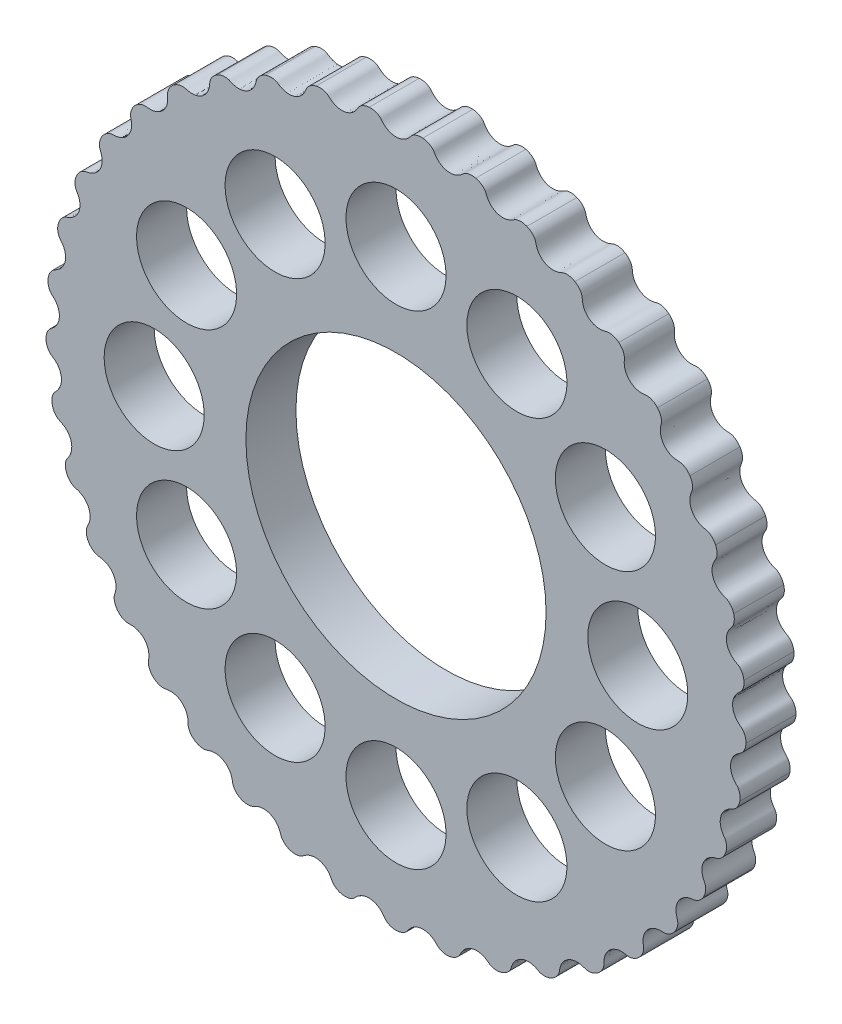
SolidWorks part; units mm, degrees
ref_plane "前视基准面" through (0, 0, 0) normal (0, 0, 1) x (1, 0, 0)
ref_plane "上视基准面" through (0, 0, 0) normal (0, 1, 0) x (1, 0, 0)
ref_plane "右视基准面" through (0, 0, 0) normal (1, 0, 0) x (0, 0, -1)
sketch "Sketch1" plane through (0, 0, 0) normal (0, 0, 1) x (1, 0, 0)
  spline S3 degree 3 number of poles 69 (-8.0377, 104.692) -> (8.0377, 104.692)
  spline S4 degree 3 number of poles 69 (8.0377, 104.692) -> (23.9246, 102.2381)
  spline S5 degree 3 number of poles 69 (23.9246, 102.2381) -> (39.2508, 97.3878)
  spline S6 degree 3 number of poles 69 (39.2508, 97.3878) -> (53.657, 90.2549)
  spline S7 degree 3 number of poles 69 (53.657, 90.2549) -> (66.8055, 81.0064)
  spline S8 degree 3 number of poles 69 (66.8055, 81.0064) -> (78.3881, 69.8592)
  spline S9 degree 3 number of poles 69 (78.3881, 69.8592) -> (88.1334, 57.0746)
  spline S10 degree 3 number of poles 69 (88.1334, 57.0746) -> (95.8129, 42.9522)
  spline S11 degree 3 number of poles 69 (95.8129, 42.9522) -> (101.2467, 27.8231)
  spline S12 degree 3 number of poles 69 (101.2467, 27.8231) -> (104.3073, 12.0418)
  spline S13 degree 3 number of poles 69 (104.3073, 12.0418) -> (104.923, -4.0218)
  spline S14 degree 3 number of poles 69 (104.923, -4.0218) -> (103.0794, -19.9911)
  spline S15 degree 3 number of poles 69 (103.0794, -19.9911) -> (98.8198, -35.4918)
  spline S16 degree 3 number of poles 69 (98.8198, -35.4918) -> (92.2438, -50.1606)
  spline S17 degree 3 number of poles 69 (92.2438, -50.1606) -> (83.5058, -63.6537)
  spline S18 degree 3 number of poles 69 (83.5058, -63.6537) -> (72.8105, -75.6548)
  spline S19 degree 3 number of poles 69 (72.8105, -75.6548) -> (60.4085, -85.8826)
  spline S20 degree 3 number of poles 69 (60.4085, -85.8826) -> (46.5906, -94.0974)
  spline S21 degree 3 number of poles 69 (46.5906, -94.0974) -> (31.6807, -100.1067)
  spline S22 degree 3 number of poles 69 (31.6807, -100.1067) -> (16.0282, -103.7695)
  spline S23 degree 3 number of poles 69 (16.0282, -103.7695) -> (0, -105.0001)
  spline S24 degree 3 number of poles 69 (0, -105.0001) -> (-16.0282, -103.7695)
  spline S25 degree 3 number of poles 69 (-16.0282, -103.7695) -> (-31.6807, -100.1067)
  spline S26 degree 3 number of poles 69 (-31.6807, -100.1067) -> (-46.5906, -94.0974)
  spline S27 degree 3 number of poles 69 (-46.5906, -94.0974) -> (-60.4085, -85.8826)
  spline S28 degree 3 number of poles 69 (-60.4085, -85.8826) -> (-72.8105, -75.6548)
  spline S29 degree 3 number of poles 69 (-72.8105, -75.6548) -> (-83.5058, -63.6537)
  spline S30 degree 3 number of poles 69 (-83.5058, -63.6537) -> (-92.2438, -50.1606)
  spline S31 degree 3 number of poles 69 (-92.2438, -50.1606) -> (-98.8198, -35.4918)
  spline S32 degree 3 number of poles 69 (-98.8198, -35.4918) -> (-103.0794, -19.9911)
  spline S33 degree 3 number of poles 69 (-103.0794, -19.9911) -> (-104.923, -4.0218)
  spline S34 degree 3 number of poles 69 (-104.923, -4.0218) -> (-104.3073, 12.0418)
  spline S35 degree 3 number of poles 69 (-104.3073, 12.0418) -> (-101.2467, 27.8231)
  spline S36 degree 3 number of poles 69 (-101.2467, 27.8231) -> (-95.8129, 42.9522)
  spline S37 degree 3 number of poles 69 (-95.8129, 42.9522) -> (-88.1334, 57.0746)
  spline S38 degree 3 number of poles 69 (-88.1334, 57.0746) -> (-78.3881, 69.8592)
  spline S39 degree 3 number of poles 69 (-78.3881, 69.8592) -> (-66.8055, 81.0064)
  spline S40 degree 3 number of poles 69 (-66.8055, 81.0064) -> (-53.657, 90.2549)
  spline S41 degree 3 number of poles 69 (-53.657, 90.2549) -> (-39.2508, 97.3878)
  spline S42 degree 3 number of poles 69 (-39.2508, 97.3878) -> (-23.9246, 102.2381)
  spline S43 degree 3 number of poles 69 (-23.9246, 102.2381) -> (-8.0377, 104.692)
  point P89 (0, 0)
sketch "Sketch2" plane through (0, 0, 0) normal (1, 0, 0) x (0, 0, -1)
  line L0 (0, 0) -> (-15, 0)
extrude "Boss-Extrude1" add sketch "Sketch1" along normal blind 15
sketch "Sketch4" plane through (0, 0, 0) normal (0, 0, -1) x (-1, 0, 0)
  circle A0 centre (0, 0) radius 45
  circle A1 centre (0, 72.5) radius 15
  circle A2 centre (36.25, 62.7868) radius 15
  circle A3 centre (62.7868, 36.25) radius 15
  circle A4 centre (72.5, 0) radius 15
  circle A5 centre (62.7868, -36.25) radius 15
  circle A6 centre (36.25, -62.7868) radius 15
  circle A7 centre (0, -72.5) radius 15
  circle A8 centre (-36.25, -62.7868) radius 15
  circle A9 centre (-62.7868, -36.25) radius 15
  circle A10 centre (-72.5, 0) radius 15
  circle A11 centre (-62.7868, 36.25) radius 15
  circle A12 centre (-36.25, 62.7868) radius 15
  point P29 (0, 0)
  dimension "D1" = 12
  dimension "D2" = 30
  dimension "D3" = 72.5
extrude "Cut-Extrude1" cut sketch "Sketch4" against normal blind 59
